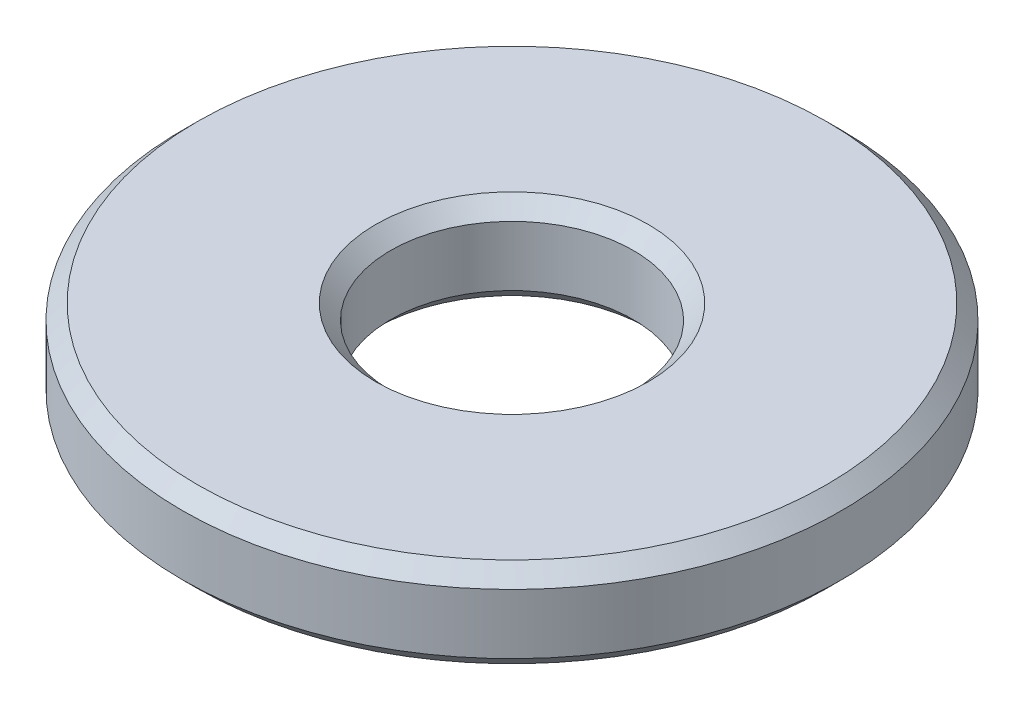
SolidWorks part; units mm, degrees
ref_plane "Front Plane" through (0, 0, 0) normal (0, 0, 1) x (1, 0, 0)
ref_plane "Top Plane" through (0, 0, 0) normal (0, 1, 0) x (1, 0, 0)
ref_plane "Right Plane" through (0, 0, 0) normal (1, 0, 0) x (0, 0, -1)
sketch "Sketch1" plane through (0, 0, 0) normal (0, 1, 0) x (1, 0, 0)
  circle A0 centre (0, 0) radius 4.05
  circle A1 centre (0, 0) radius 11
  dimension "D1" = 8.1
  dimension "D2" = 22
extrude "Boss-Extrude1" add sketch "Sketch1" along normal mid plane 3
chamfer "Chamfer1" distance 0.5 angle 45 4 edges at (0, -1.5, 11) (0, 1.5, 11) (0, -1.5, 4.05) (0, 1.5, 4.05)
